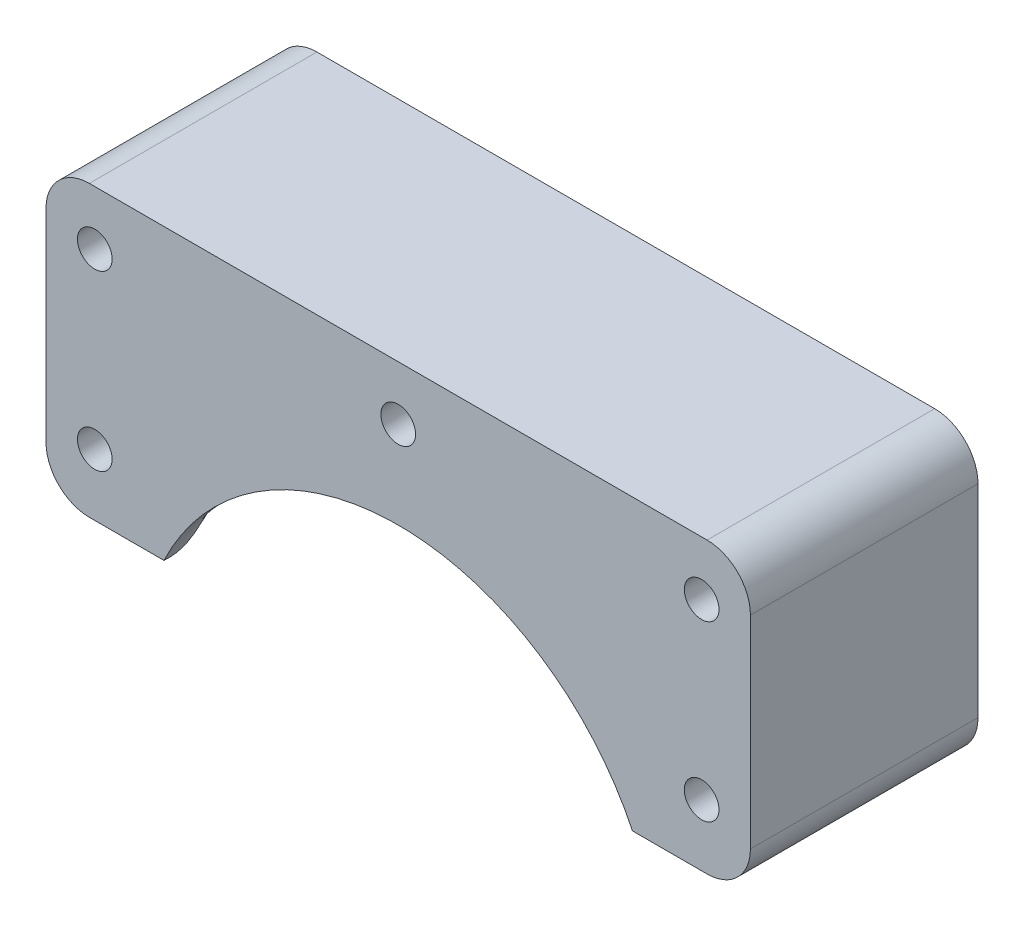
SolidWorks part; units mm, degrees
ref_plane "Front Plane" through (0, 0, 0) normal (0, 0, 1) x (1, 0, 0)
ref_plane "Top Plane" through (0, 0, 0) normal (0, 1, 0) x (1, 0, 0)
ref_plane "Right Plane" through (0, 0, 0) normal (1, 0, 0) x (0, 0, -1)
sketch "Sketch1" plane through (0, 0, 0) normal (0, 0, 1) x (1, 0, 0)
  line L0 (0, 0) -> (-24.8986, 10.3133) construction
  line L1 (0, 0) -> (24.8986, 10.3133) construction
  line L2 (24.8986, 10.3133) -> (-24.8986, 10.3133) construction
  line L3 (0, 24.35) -> (0, 26.95) construction
  line L4 (-24.8986, 10.3133) -> (-32.5, 10.3133)
  line L5 (-32.5, 10.3133) -> (-32.5, 37)
  line L6 (-32.5, 37) -> (32.5, 37)
  line L7 (24.8986, 10.3133) -> (32.5, 10.3133)
  line L8 (32.5, 10.3133) -> (32.5, 37)
  line L9 (0, 0) -> (0, 32) construction
  line L10 (0, 32) -> (28, 32) construction
  circle A0 centre (0, 0) radius 24.35 construction
  circle A1 centre (0, 0) radius 26.95
  circle A2 centre (28, 32) radius 1.6
  circle A3 centre (0, 32) radius 1.6
  circle A4 centre (-28, 32) radius 1.6
  circle A5 centre (28, 16) radius 1.6
  circle A6 centre (-28, 16) radius 1.6
  dimension "D1" = 48.7
  dimension "D3" = 2.6
  dimension "D8" = 3.2
  dimension "D9" = 3.2
  dimension "D10" = 16
  dimension "D2" = 135
  dimension "D4" = 37
  dimension "D5" = 65
  dimension "D6" = 28
  dimension "D7" = 32
extrude "Boss-Extrude1" add sketch "Sketch1" along normal mid plane 21 contours A1 L7 L8 L6 L5 L4
sketch "Sketch2" plane through (0, 0, 0) normal (1, 0, 0) x (0, 0, -1)
  line L0 (0, 0) -> (-22.3231, 0) construction
  line L1 (10.5, 10.3133) -> (10.5, 26.95) construction
  line L2 (-10.5, 26.9483) -> (-6.6767, 26.9483)
  line L3 (10.5, 26.9483) -> (4.5, 26.9483)
  line L4 (4.5, 26.9483) -> (-2.1767, 26.9483)
  line L5 (-10.5, 10.3133) -> (10.5, 10.3133) construction
  line L6 (-10.5, 10.3133) -> (-10.5, 26.9483) construction
  line L7 (-10.5, 26.9483) -> (10.5, 26.9483) construction
  line L8 (10.5, 10.3133) -> (10.5, 26.9483) construction
  line L9 (10.5, 10.3133) -> (10.5, 37) construction
  line L10 (-2.1767, 26.9483) -> (-6.6767, 26.9483)
  line L11 (-6.6767, 26.9483) -> (-6.6767, 26.2483) construction
  line L12 (4.5, 26.9483) -> (4.5, 26.2483) construction
  line L13 (-10.5, 26.95) -> (-10.5, 10.3133) construction
  line L14 (10.5, 24.9483) -> (10.5, 26.9483)
  line L15 (-10.5, 24.9483) -> (-10.5, 26.9483)
  spline S0 degree 3 poles (-10.5, 24.9483) (-8.4905, 25.7565) (-1.5563, 28.0446) (5.7798, 25.965) (10.5, 24.9483) knots 0 0 0 0 0.306248 1 1 1 1
  dimension "D1" = 16.635
  dimension "D2" = 6
  dimension "D3" = 4.5
  dimension "D4" = 0.7
  dimension "D5" = 0.7
  dimension "D6" = 2
  dimension "D7" = 2
  dimension "D8" = 0.2
revolve "Revolve1" [suppressed] add sketch "Sketch2" angle 67.5 about L0
fillet "Fillet1" radius 4 4 edges at (32.5, 37, 0) (-32.5, 10.3133, 0) (-32.5, 37, 0) (32.5, 10.3133, 0)
chamfer "Chamfer2" [suppressed] distance 1 angle 45
sketch "Sketch3" plane through (0, 0, 0) normal (1, 0, 0) x (0, 0, -1)
  line L2 (0, 0) -> (7.6872, 0) construction
  circle A1 centre (-0.047, 25.2604) radius 2
  circle A2 centre (-0.047, 25.2604) radius 0.4
  spline S0 degree 3 poles (9.0434, 25.3816) (6.0798, 25.8564) (-0.0311, 28.6626) (-6.1906, 25.8599) (-9.1188, 25.3688) knots 0 0 0 0 0.500307 1 1 1 1
  dimension "D1" = 4
  dimension "D2" = 0.8
revolve "Revolve2" [suppressed] add sketch "Sketch3" angle 67.5 about L2
sketch "Sketch4" plane through (0, 0, -10.5) normal (0, 0, -1) x (-1, 0, 0)
  circle A0 centre (-28, 32) radius 2.8
  circle A1 centre (0, 32) radius 2.8
  circle A2 centre (28, 32) radius 2.8
  circle A3 centre (-28, 16) radius 2.8
  circle A4 centre (28, 16) radius 2.8
  dimension "D1" = 5.6
extrude "Cut-Extrude1" cut sketch "Sketch4" against normal blind 5.5
chamfer "Chamfer3" distance 0.6 angle 45 4 edges at (-30.8, 32, -10.5) (-2.8, 32, -10.5) (25.2, 32, -10.5) (25.2, 16, -10.5)
chamfer "Chaflán1" [suppressed] distance 0.6 angle 45
sketch "Croquis1" plane through (0, 0, 0) normal (1, 0, 0) x (0, 0, -1)
  line L0 (10.5, 26.95) -> (-10.5, 26.95)
  line L1 (10.5, 10.3133) -> (10.5, 26.95) construction
  line L2 (-10.5, 14.3133) -> (-10.5, 33) construction
  line L3 (-10.5, 26.95) -> (-10.5, 10.3133) construction
  line L4 (-10.5, 26.95) -> (-10.5, 23.95)
  line L5 (10.5, 26.95) -> (10.5, 23.95)
  circle A0 centre (0, 24.85) radius 2 construction
  spline S0 degree 3 poles (10.5, 23.95) (7.1392, 23.6956) (0, 30.0044) (-7.1392, 23.6956) (-10.5, 23.95) knots 0 0 0 0 0.5 1 1 1 1
  point P13 (0, 26.85)
  point P15 (0, 26.95)
  dimension "D8" = 4
  dimension "D1" = 0.1
  dimension "D2" = 0.7
  dimension "D3" = 0.7
  dimension "D4" = 3
  dimension "D5" = 3
  dimension "D6" = 3
  dimension "D7" = 3
revolve "Revolución1" add sketch "Croquis1" angle 67.5 about axis through (0, 0, 10.5) along (0, 0, -1) other way angle 67.5
sketch "Croquis2" plane through (0, 0, 0) normal (1, 0, 0) x (0, 0, -1)
  circle A0 centre (0, 24.85) radius 2
  circle A1 centre (0, 24.85) radius 0.4
  dimension "D1" = 4
  dimension "D2" = 0.8
revolve "Revolución2" [suppressed] add sketch "Croquis2" angle 67.5
sketch "Croquis4" [suppressed] plane through (0, 0, -10.5) normal (0, 0, -1) x (-1, 0, 0)
  text T0 "<b>N</b>" font "Century Gothic" height in points 16
extrude "Cortar-Extruir2" [suppressed] cut sketch "Croquis4" against normal blind 1
fillet "Redondeo1" [suppressed] radius 0.2
sketch "Croquis5" plane through (0, 0, -10.5) normal (0, 0, -1) x (-1, 0, 0)
  text T0 "<b>A</b>" font "Century Gothic" height in points 16
extrude "Cortar-Extruir3" cut sketch "Croquis5" against normal blind 1
sketch "Croquis6" plane through (0, 0, -10.5) normal (0, 0, -1) x (-1, 0, 0)
  line L1 (-24.8986, 10.3133) -> (24.8986, 10.3133)
  line L2 (-24.8986, 10.3133) -> (-24.8986, -4.7889)
  line L3 (-24.8986, -4.7889) -> (24.8986, -4.7889)
  line L4 (24.8986, 10.3133) -> (24.8986, -4.7889)
extrude "Cortar-Extruir4" cut sketch "Croquis6" against normal through all both and the other way through all
